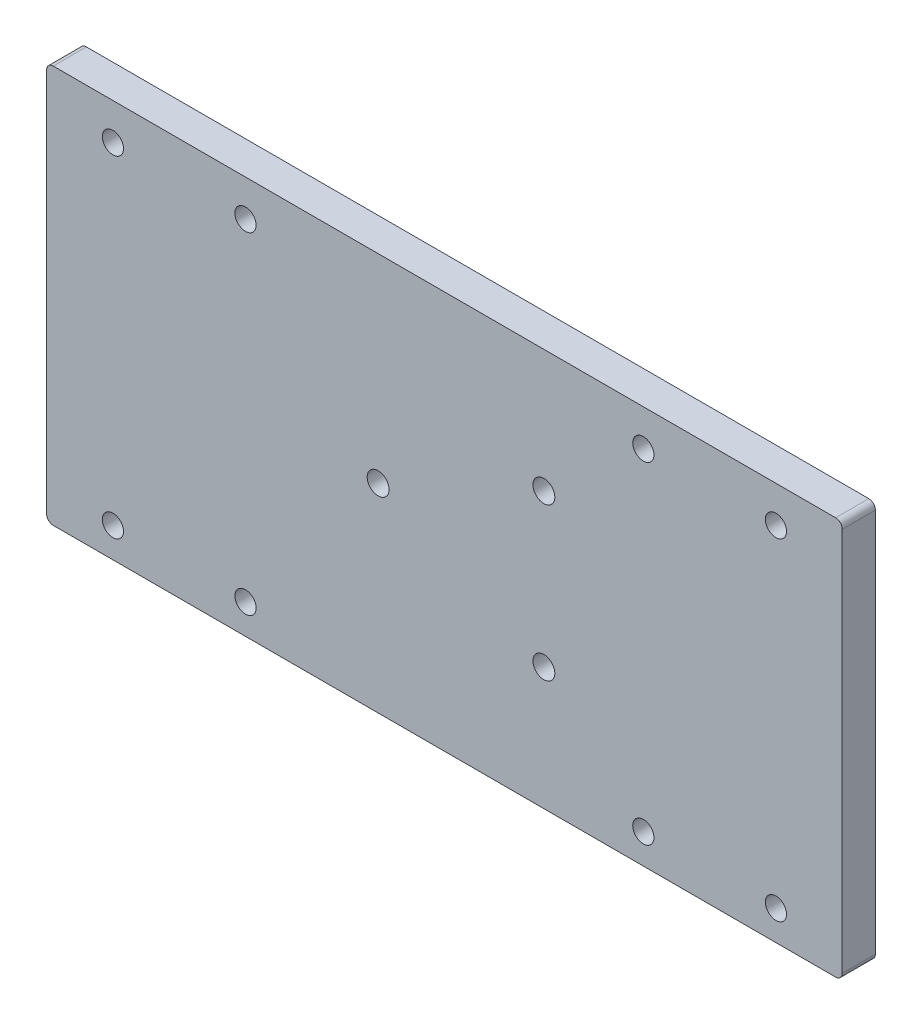
SolidWorks part; units mm, degrees
ref_plane "前视基准面" through (0, 0, 0) normal (0, 0, 1) x (1, 0, 0)
ref_plane "上视基准面" through (0, 0, 0) normal (0, 1, 0) x (1, 0, 0)
ref_plane "右视基准面" through (0, 0, 0) normal (1, 0, 0) x (0, 0, -1)
other "Configuration Table"
sketch "草图1" plane through (0, 0, 0) normal (0, 0, 1) x (1, 0, 0)
  line L0 (12, -49) -> (12, 0) construction
  line L1 (20, 5.5) -> (-100, 5.5)
  line L2 (20, 5.5) -> (20, -54.5)
  line L3 (20, -54.5) -> (-100, -54.5)
  line L4 (-100, 5.5) -> (-100, -54.5)
  line L5 (12, -52.5) -> (12, -45.5) construction
  line L6 (12, -3.5) -> (12, 3.5) construction
  line L7 (12, -24.5) -> (23.0806, -24.5) construction
  point P12 (12, -24.5)
  dimension "D3" = 20
  dimension "D1" = 60
  dimension "D2" = 120
extrude "凸台-拉伸1" add sketch "草图1" along normal blind 5
sketch "草图2" plane through (0, 0, 5) normal (0, 0, 1) x (1, 0, 0)
  line L0 (-25, -13) -> (-25, -36) construction
  line L2 (-50, -24.5) -> (-25, -13) construction
  circle A0 centre (-25, -13) radius 1.65
  circle A1 centre (-50, -24.5) radius 1.65
  circle A3 centre (-25, -36) radius 1.65
  point P8 (-105.8081, -0.5296)
  dimension "D1" = 3.3
  dimension "D2" = 23
  dimension "D3" = 25
  dimension "D4" = 11.5
  dimension "D5" = 25
  dimension "D6" = 13
extrude "切除-拉伸1" cut sketch "草图2" against normal up to next
sketch "草图4" plane through (0, 0, 0) normal (0, 0, -1) x (-1, 0, 0)
  line L0 (90, 0) -> (70, 0) construction
  line L1 (70, 0) -> (10, 0) construction
  line L2 (10, 0) -> (-10, 0) construction
  line L3 (-10, 0) -> (-10, -50) construction
  line L4 (-10, -50) -> (10, -50) construction
  line L5 (10, -50) -> (70, -50) construction
  line L6 (70, -50) -> (90, -50) construction
  line L7 (10, 0) -> (10, -50) construction
  line L8 (70, 0) -> (70, -50) construction
  line L9 (90, 0) -> (90, -50) construction
  circle A0 centre (90, 0) radius 1.6
  circle A1 centre (70, 0) radius 1.6
  circle A2 centre (70, -50) radius 1.6
  circle A3 centre (90, -50) radius 1.6
  circle A4 centre (10, -50) radius 1.6
  circle A5 centre (-10, -50) radius 1.6
  circle A6 centre (-10, 0) radius 1.6
  circle A7 centre (10, 0) radius 1.6
  dimension "D1" = 3.2
  dimension "D2" = 50
  dimension "D3" = 10
  dimension "D4" = 10
  dimension "D5" = 60
  dimension "D6" = 20
extrude "切除-拉伸2" cut sketch "草图4" against normal up to next
sketch "草图5" plane through (0, 0, 5) normal (0, 0, 1) x (1, 0, 0)
  line L0 (-20, -54.5) -> (-20, 5.5) construction
  line L1 (-100, -54.5) -> (20, -54.5) construction
  line L2 (20, 5.5) -> (-100, 5.5) construction
  line L3 (20, -54.5) -> (20, 5.5) construction
  line L4 (-10, -24.5) -> (20, -24.5) construction
  circle A0 centre (-20, -43.5) radius 1.65
  circle A1 centre (-10, -24.5) radius 1.65
  circle A2 centre (-20, -5.5) radius 1.65
  dimension "D4" = 3.3
  dimension "D1" = 40
  dimension "D2" = 11
  dimension "D3" = 11
  dimension "D5" = 10
fillet "圆角1" radius 1 4 edges at (-100, -54.5, 2.5) (-100, 5.5, 2.5) (20, -54.5, 2.5) (20, 5.5, 2.5)
